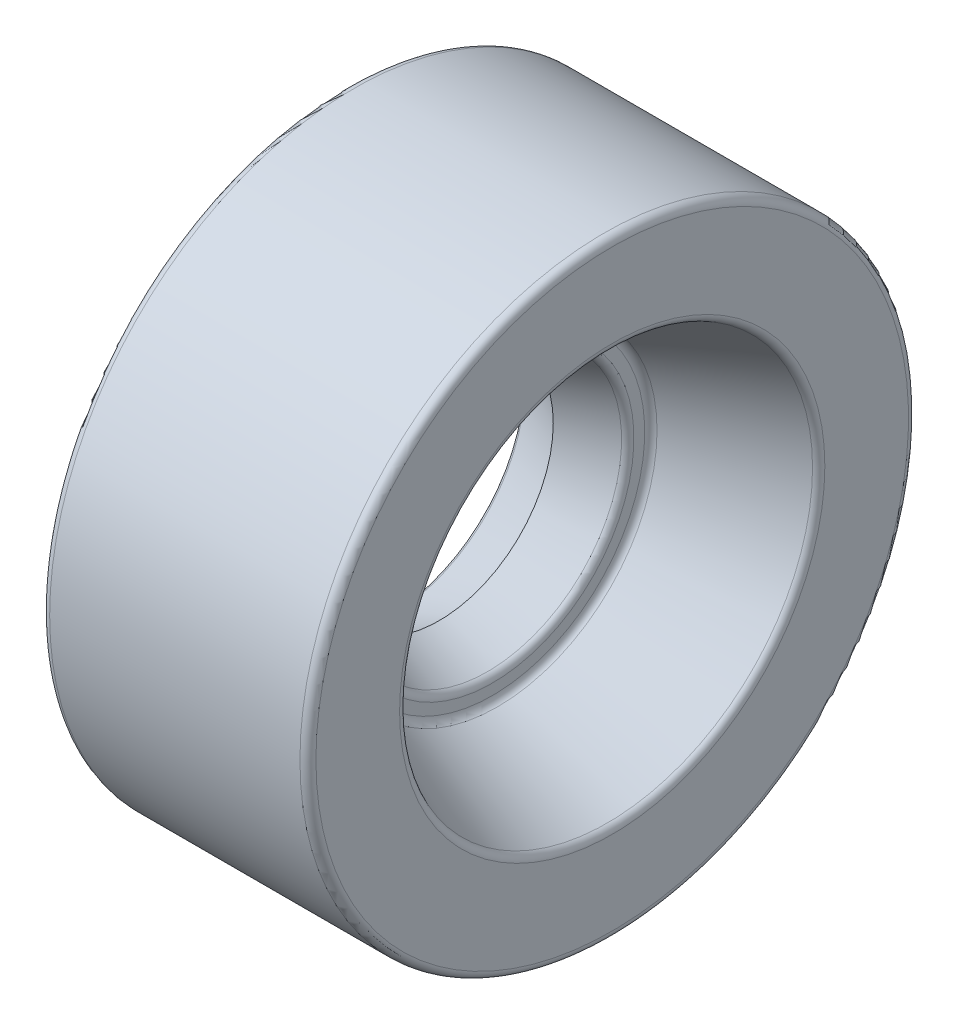
SolidWorks part; units mm, degrees
ref_plane "Přední rovina" through (0, 0, 0) normal (0, 0, 1) x (1, 0, 0)
ref_plane "Vrchní rovina" through (0, 0, 0) normal (0, 1, 0) x (1, 0, 0)
ref_plane "Pravá rovina" through (0, 0, 0) normal (1, 0, 0) x (0, 0, -1)
sketch "Skica1" plane through (0, 0, 0) normal (0, 0, 1) x (1, 0, 0)
  line L0 (0, 0) -> (4.55, 0) construction
  line L1 (-2.45, 8) -> (4.55, 8)
  line L2 (4.55, 8) -> (4.55, 5.45)
  line L3 (4.55, 5.45) -> (1.4, 4.1452)
  line L4 (1.4, 4.1452) -> (1.4, 3.5799)
  line L5 (1.4, 3.5799) -> (0, 3)
  line L6 (0, 3) -> (-1.4, 3.5799)
  line L7 (-1.4, 3.5799) -> (-1.4, 4.75)
  line L8 (-1.4, 4.75) -> (-0.525, 4.75)
  line L9 (0.525, 4.75) -> (1.2138, 4.75)
  line L10 (1.2138, 4.75) -> (3.5, 5.697)
  line L11 (3.5, 5.697) -> (3.5, 6.6382)
  line L12 (3.5, 6.6382) -> (-2.45, 6.95)
  line L13 (-2.45, 6.95) -> (-2.45, 8)
  line L14 (0, 4.75) -> (0, 3) construction
  arc A0 (-0.525, 4.75) -> (0.525, 4.75) centre (0, 4.75) ccw
  dimension "D7" = 0.525
  dimension "D1" = 16
  dimension "D2" = 7
  dimension "D3" = 4.55
  dimension "D4" = 6
  dimension "D5" = 1.05
  dimension "D6" = 1.05
  dimension "D8" = 1.75
  dimension "D9" = 0.63
  dimension "D10" = 1.4
  dimension "D11" = 135
  dimension "D12" = 2.45
  dimension "D13" = 3
revolve "Otočit kolem osy1" add sketch "Skica1" angle 360 about L0
fillet "Zaoblit1" radius 0.21 11 edges at (-1.4, 0, 3.5799) (-1.4, 0, 4.75) (1.2138, 0, 4.75) (3.5, 0, 5.697) (3.5, 0, 6.6382) (-2.45, 0, 6.95) (-2.45, 0, 8) (4.55, 0, 8) (4.55, 0, 5.45) (1.4, 0, 4.1452) (1.4, 0, 3.5799)
sketch "Skica2" plane through (0, 0, 0) normal (0, 1, 0) x (1, 0, 0)
  circle A0 centre (0, 4.75) radius 0.525
  arc A1 (-0.525, 4.75) -> (0.525, 4.75) centre (0, 4.75) ccw construction
  circle A2 centre (0, 4.75) radius 0.105
  circle A3 centre (0, 4.75) radius 0.4255
  dimension "D1" = 0.0995
  dimension "D2" = 0.21
revolve "Otočit kolem osy3" add sketch "Skica2" angle 360 about axis through (0, 0, 0) along (1, 0, 0)
equation "\"D3@Skica1\"=\"D2@Skica1\" * 0.65"
equation "\"D5@Skica1\" = \"D2@Skica1\" * 0.15"
equation "\"D6@Skica1\" = \"D2@Skica1\" * 0.15"
equation "\"D7@Skica1\" = \"D2@Skica1\" * 0.075"
equation "\"D8@Skica1\" = \"D2@Skica1\" * 0.25"
equation "\"D9@Skica1\" = \"D5@Skica1\"*0.6"
equation "\"D10@Skica1\" = \"D8@Skica1\" * 0.8"
equation "\"D12@Skica1\" = \"D8@Skica1\" * 1.4"
equation "\"D1@Zaoblit1\" = \"D2@Skica1\" * 0.03"
equation "\"D2@Skica2\" = \"D7@Skica1\"*0.4"
